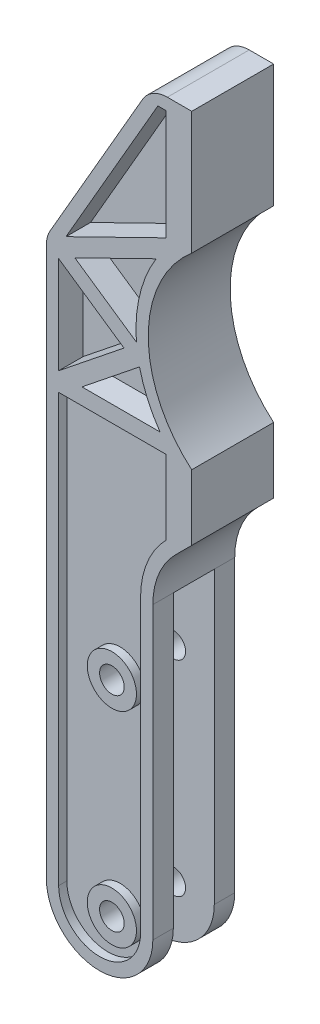
SolidWorks part; units mm, degrees
ref_plane "Front Plane" through (0, 0, 0) normal (0, 0, 1) x (1, 0, 0)
ref_plane "Top Plane" through (0, 0, 0) normal (0, 1, 0) x (1, 0, 0)
ref_plane "Right Plane" through (0, 0, 0) normal (1, 0, 0) x (0, 0, -1)
sketch "Sketch1" plane through (0, 0, 0) normal (0, 0, 1) x (1, 0, 0)
  line L0 (0, 0) -> (0, 90) construction
  line L1 (0, 90) -> (-5, 90) construction
  line L2 (-5, 90) -> (-17.75, 67.9164) construction
  line L3 (-17.75, 67.9164) -> (-17.75, 0) construction
  line L4 (-17.75, 0) -> (0, 0) construction
  line L5 (0, 88.5) -> (-2, 86.5)
  line L6 (-2, 90) -> (0, 90) construction
  line L7 (-2, 90) -> (-2, 75) construction
  line L8 (-2, 75) -> (0, 75) construction
  line L9 (0, 90) -> (0, 75) construction
  line L10 (-2, 86.5) -> (0, 84.5)
  line L11 (0, 84.5) -> (-2, 82.5)
  line L12 (-2, 82.5) -> (0, 80.5)
  line L13 (0, 80.5) -> (-2, 78.5)
  line L14 (-2, 78.5) -> (0, 76.5)
  line L15 (0, 64.3) -> (-17.75, 64.3) construction
  line L16 (0, 88.5) -> (0, 90)
  line L17 (0, 90) -> (-5, 90)
  line L18 (0, 75) -> (0, 76.5)
  line L19 (-2, 50.1) -> (0, 52.1)
  line L20 (0, 48.1) -> (-2, 50.1)
  line L21 (-2, 46.1) -> (0, 48.1)
  line L22 (0, 44.1) -> (-2, 46.1)
  line L23 (-2, 42.1) -> (0, 44.1)
  line L24 (-5, 90) -> (-17.75, 67.9164)
  line L25 (-17.75, 67.9164) -> (-17.75, 0)
  line L26 (-4.75, 0) -> (-4.75, 35.4609)
  line L27 (-9.75, 0) -> (-9.75, 25) construction
  arc A0 (0, 75) -> (0, 52.1) centre (9.6901, 63.55) ccw
  arc A1 (-17.75, 0) -> (-4.75, 0) centre (-11.25, 0) ccw
  arc A2 (-4.75, 35.4609) -> (-2, 42.1) centre (4.6391, 35.4609) cw
  circle A3 centre (-9.75, 0) radius 1.5
  circle A4 centre (-9.75, 25) radius 1.5
  dimension "D11" = 15
  dimension "D12" = 6.5
  dimension "D13" = 5
  dimension "D15" = 25
  dimension "D14" = 3
  dimension "D1" = 5
  dimension "D2" = 90
  dimension "D3" = 30
  dimension "D4" = 17.75
  dimension "D5" = 2
  dimension "D6" = 15
  dimension "D7" = 1.5
  dimension "D8" = 3.5
  dimension "D10" = 24.2
  dimension "D9" = 3
extrude "Boss-Extrude1" add sketch "Sketch1" along normal mid plane 10
sketch "Sketch2" plane through (0, 0, 0) normal (0, 0, 1) x (1, 0, 0)
  line L0 (-15, -8.4108) -> (-15, 23.5892)
  line L1 (-4.75, 0) -> (-4.75, 35.4609) construction
  line L2 (-15, -8.4108) -> (-4.75, -8.4108)
  line L3 (-4.75, -8.4108) -> (-4.75, 35.4609)
  arc A1 (-15, 23.5892) -> (-4.75, 35.4609) centre (-3, 23.5892) cw
  dimension "D2" = 12
  dimension "D1" = 10.25
  dimension "D3" = 32
extrude "Cut-Extrude1" cut sketch "Sketch2" against normal mid plane 5
sketch "Sketch3" plane through (0, 0, 5) normal (0, 0, 1) x (1, 0, 0)
  line L0 (-3.1276, 88.5) -> (-3.1276, 43.0931)
  line L34 (-2.1213, 88.5) -> (-4.134, 88.5)
  line L35 (-4.134, 88.5) -> (-16.25, 67.5144)
  line L36 (-16.25, 67.5144) -> (-16.25, 0)
  line L37 (-6.25, 0) -> (-6.25, 35.4609)
  line L38 (-3.0607, 43.1607) -> (-2.1213, 44.1)
  line L39 (-2.1213, 44.1) -> (-4.1213, 46.1)
  line L40 (-4.1213, 46.1) -> (-2.1213, 48.1)
  line L41 (-2.1213, 48.1) -> (-4.1213, 50.1)
  line L42 (-4.1213, 50.1) -> (-2.1565, 52.0648)
  line L43 (-1.5, 75.6757) -> (-1.5, 75.8787)
  line L44 (-1.5, 75.8787) -> (-4.1213, 78.5)
  line L45 (-4.1213, 78.5) -> (-2.1213, 80.5)
  line L46 (-2.1213, 80.5) -> (-4.1213, 82.5)
  line L47 (-4.1213, 82.5) -> (-2.1213, 84.5)
  line L48 (-2.1213, 84.5) -> (-4.1213, 86.5)
  line L49 (-4.1213, 86.5) -> (-2.1213, 88.5)
  line L50 (-2.1213, 88.5) -> (-4.134, 88.5)
  line L51 (-4.134, 88.5) -> (-16.25, 67.5144)
  line L52 (-16.25, 67.5144) -> (-16.25, 0)
  line L53 (-6.25, 0) -> (-6.25, 35.4609)
  line L54 (-3.0607, 43.1607) -> (-2.1213, 44.1)
  line L55 (-2.1213, 44.1) -> (-4.1213, 46.1) construction
  line L56 (-4.1213, 46.1) -> (-2.1213, 48.1) construction
  line L57 (-2.1213, 48.1) -> (-4.1213, 50.1) construction
  line L58 (-4.1213, 50.1) -> (-2.1565, 52.0648) construction
  line L59 (-1.5, 75.6757) -> (-1.5, 75.8787) construction
  line L60 (-1.5, 75.8787) -> (-4.1213, 78.5) construction
  line L61 (-4.1213, 78.5) -> (-2.1213, 80.5) construction
  line L62 (-2.1213, 80.5) -> (-4.1213, 82.5) construction
  line L63 (-4.1213, 82.5) -> (-2.1213, 84.5) construction
  line L64 (-2.1213, 84.5) -> (-4.1213, 86.5) construction
  line L65 (-4.1213, 86.5) -> (-2.1213, 88.5) construction
  arc A6 (-16.25, 0) -> (-6.25, 0) centre (-11.25, 0) ccw
  arc A7 (-3.0607, 43.1607) -> (-6.25, 35.4609) centre (4.6391, 35.4609) ccw
  arc A8 (-1.5, 75.6757) -> (-2.1565, 52.0648) centre (9.6901, 63.55) ccw
  arc A9 (-16.25, 0) -> (-6.25, 0) centre (-11.25, 0) ccw
  arc A10 (-3.0607, 43.1607) -> (-6.25, 35.4609) centre (4.6391, 35.4609) ccw
  arc A11 (-1.5, 75.6757) -> (-2.1565, 52.0648) centre (9.6901, 63.55) ccw
  circle M20 centre (-9.75, 0) radius 1.5
  circle M41 centre (-9.75, 25) radius 1.5
  dimension "D1" = 1.5
extrude "Cut-Extrude3" cut sketch "Sketch3" against normal blind 1 contours A11 L0 L50 L51 L52 A9 L53 A10 M41 M20
sketch "Sketch4" plane through (0, 0, 4) normal (0, 0, 1) x (1, 0, 0)
  circle A0 centre (-9.75, 25) radius 1.5 construction
  circle A1 centre (-9.75, 25) radius 1.5
  circle A2 centre (-9.75, 0) radius 1.5 construction
  circle A3 centre (-9.75, 0) radius 1.5
extrude "Extrude-Thin1" add sketch "Sketch4" along normal blind 1 thin
sketch "Sketch5" plane through (0, 0, 4) normal (0, 0, 1) x (1, 0, 0)
  line L0 (-3.1276, 53.1598) -> (-16.25, 53.1598)
  line L6 (-3.1276, 73.9402) -> (-3.1276, 88.5)
  line L7 (-3.1276, 88.5) -> (-4.134, 88.5)
  line L8 (-4.134, 88.5) -> (-16.25, 67.5144)
  line L9 (-16.25, 67.5144) -> (-16.25, 0)
  line L10 (-6.25, 0) -> (-6.25, 35.4609)
  line L11 (-3.1276, 43.0931) -> (-3.1276, 53.1598)
  line L12 (-3.1276, 73.9402) -> (-3.1276, 88.5)
  line L13 (-3.1276, 88.5) -> (-4.134, 88.5)
  line L14 (-4.134, 88.5) -> (-16.25, 67.5144)
  line L15 (-16.25, 67.5144) -> (-16.25, 0)
  line L16 (-6.25, 0) -> (-6.25, 35.4609)
  line L17 (-3.1276, 43.0931) -> (-3.1276, 53.1598) construction
  arc A3 (-3.1276, 73.9402) -> (-3.1276, 53.1598) centre (9.6901, 63.55) ccw
  arc A4 (-16.25, 0) -> (-6.25, 0) centre (-11.25, 0) ccw
  arc A5 (-3.1276, 43.0931) -> (-6.25, 35.4609) centre (4.6391, 35.4609) ccw
  arc A6 (-3.1276, 73.9402) -> (-3.1276, 53.1598) centre (9.6901, 63.55) ccw
  arc A7 (-16.25, 0) -> (-6.25, 0) centre (-11.25, 0) ccw
  arc A8 (-3.1276, 43.0931) -> (-6.25, 35.4609) centre (4.6391, 35.4609) ccw construction
  arc M11 (-3.1276, 53.1598) -> (-3.1276, 73.9402) centre (9.6901, 63.55) cw
  line M12 (-3.1276, 73.9402) -> (-3.1276, 88.5)
  line M13 (-3.1276, 88.5) -> (-4.134, 88.5)
  line M14 (-4.134, 88.5) -> (-16.25, 67.5144)
  line M15 (-16.25, 67.5144) -> (-16.25, 0)
  dimension "D1" = 0
extrude "Cut-Extrude4" cut sketch "Sketch5" against normal blind 2 contours L0 M11 M12 M13 M14 M15
sketch "Sketch6" plane through (0, 0, 5) normal (0, 0, 1) x (1, 0, 0)
  line L0 (-3.1276, 53.1598) -> (-16.25, 53.1598)
  line L1 (-16.25, 67.5144) -> (-16.25, 0) construction
  line L2 (-16.25, 67.5144) -> (-16.25, 53.1598) construction
  line L3 (-16.25, 53.1598) -> (-6.5945, 60.8925)
  line L4 (-6.5945, 60.8925) -> (-16.25, 67.5144)
  line L5 (-16.25, 67.5144) -> (-3.1276, 73.9402)
  arc A0 (-3.1276, 73.9402) -> (-3.1276, 53.1598) centre (9.6901, 63.55) ccw construction
extrude "Extrude-Thin2" add sketch "Sketch6" against normal up to body thin thin type mid plane wall 2
sketch "Sketch7" plane through (0, 0, 5) normal (0, 0, 1) x (1, 0, 0)
  line L0 (-3.1276, 73.9402) -> (-3.5674, 74.8383) construction
  line L1 (-3.1276, 73.9402) -> (-3.5674, 74.8383)
  line L2 (-3.5674, 74.8383) -> (-3.1276, 75.0536)
  line L3 (-3.1276, 73.9402) -> (-3.1276, 88.5) construction
  line L4 (-3.1276, 75.0536) -> (-3.1276, 73.9402)
  line L5 (-3.5674, 74.8383) -> (-15.3538, 69.0668) construction
extrude "Boss-Extrude2" add sketch "Sketch7" against normal up to next
mirror "Mirror2" about plane through (0, 0, 0) normal (0, 0, 1) of "Boss-Extrude2", "Extrude-Thin2", "Cut-Extrude4", "Extrude-Thin1", "Cut-Extrude3", "Cut-Extrude1"
fillet "Fillet1" radius 3.5 2 edges at (-5, 90, 0) (-17.75, 67.9164, 0)
sketch "Sketch11" plane through (0, 0, 5) normal (0, 0, 1) x (1, 0, 0)
  line L0 (0, 88.5) -> (-2, 86.5)
  line L1 (-2, 86.5) -> (0, 84.5)
  line L2 (0, 84.5) -> (-2, 82.5)
  line L3 (-2, 82.5) -> (0, 80.5)
  line L4 (0, 80.5) -> (-2, 78.5)
  line L5 (-2, 78.5) -> (0, 76.5)
  line L6 (0, 76.5) -> (0, 88.5)
  line L7 (0, 52.1) -> (-2, 50.1)
  line L8 (-2, 50.1) -> (0, 48.1)
  line L9 (0, 48.1) -> (-2, 46.1)
  line L10 (-2, 46.1) -> (0, 44.1)
  line L11 (0, 44.1) -> (0, 52.1)
  line M29 (0, 44.1) -> (-2, 46.1)
  line M30 (-2, 46.1) -> (0, 48.1)
  line M31 (0, 48.1) -> (-2, 50.1)
  line M32 (-2, 50.1) -> (0, 52.1)
  line M35 (0, 76.5) -> (-2, 78.5)
  line M36 (-2, 78.5) -> (0, 80.5)
  line M37 (0, 80.5) -> (-2, 82.5)
  line M38 (-2, 82.5) -> (0, 84.5)
  line M39 (0, 84.5) -> (-2, 86.5)
  line M40 (-2, 86.5) -> (0, 88.5)
extrude "Boss-Extrude8" add sketch "Sketch11" against normal blind 10 contours L6 M39 M40 | L6 M37 M38 | L6 M35 M36 | L11 M31 M32 | L11 M29 M30
